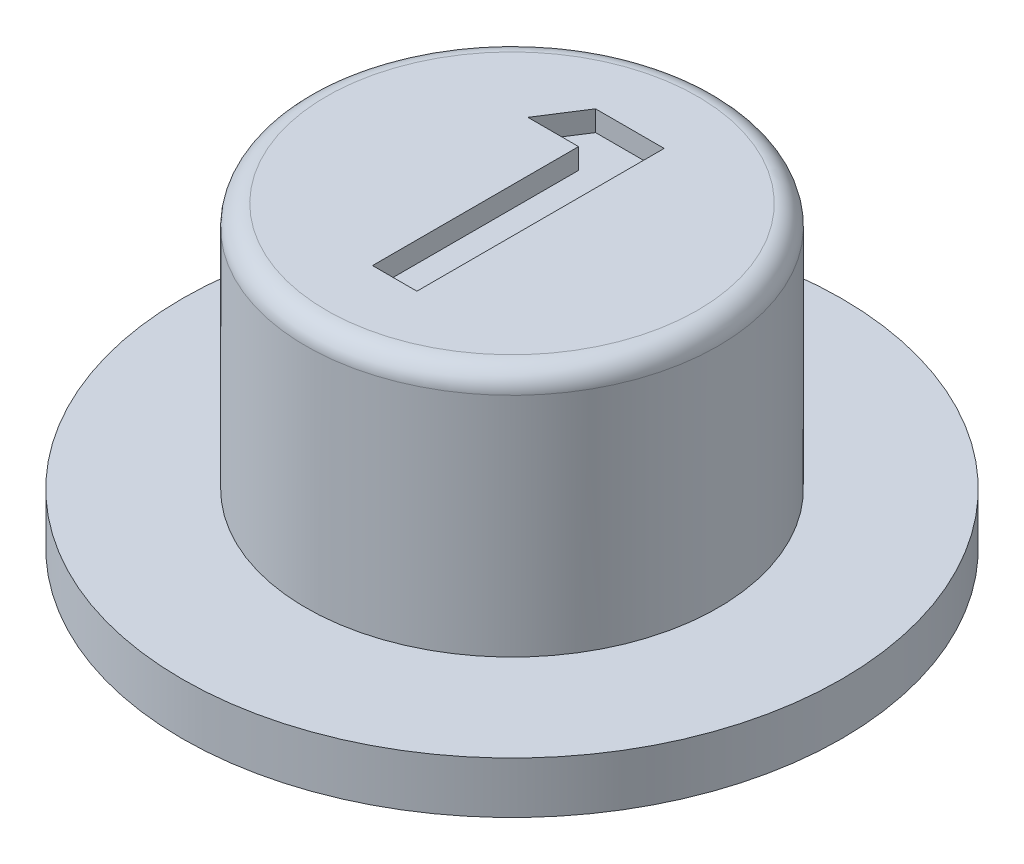
SolidWorks part; units mm, degrees
ref_plane "Front Plane" through (0, 0, 0) normal (0, 0, 1) x (1, 0, 0)
ref_plane "Top Plane" through (0, 0, 0) normal (0, 1, 0) x (1, 0, 0)
ref_plane "Right Plane" through (0, 0, 0) normal (1, 0, 0) x (0, 0, -1)
sketch "Sketch1" plane through (0, 0, 0) normal (0, 0, 1) x (1, 0, 0)
  line L1 (0, 7.25) -> (5, 7.25)
  line L2 (5, 7.25) -> (5, 1.25)
  line L3 (5, 1.25) -> (8, 1.25)
  line L4 (8, 1.25) -> (8, 0)
  line L6 (0, 7.25) -> (0, 6.9292) construction
  line L7 (0, 7.25) -> (0, 0)
  line L10 (0, 0) -> (8, 0)
  dimension "D1" = 5
  dimension "D2" = 3
  dimension "D3" = 6
  dimension "D4" = 1.25
revolve "Revolve1" add sketch "Sketch1" angle 360 about L6
sketch "Sketch2" plane through (0, 0, 0) normal (0, -1, 0) x (1, 0, 0)
  line L1 (-1.25, -1.75) -> (1.25, -1.75)
  line L2 (-1.25, -1.75) -> (-1.25, 1.75)
  line L3 (-1.25, 1.75) -> (1.25, 1.75)
  line L4 (1.25, -1.75) -> (1.25, 1.75)
  line L5 (-1.25, -1.75) -> (1.25, 1.75) construction
  line L6 (-1.25, 1.75) -> (1.25, -1.75) construction
  point P0 (0, 0)
  dimension "D1" = 2.5
  dimension "D2" = 3.5
extrude "Cut-Extrude1" cut sketch "Sketch2" against normal blind 3.5 contours L3 L4 L1 L2
fillet "Fillet1" radius 0.5 1 edges at (-5, 7.25, 0)
sketch "Sketch3" plane through (0, 7.25, 0) normal (0, 1, 0) x (1, 0, 0)
  line L0 (-3.3541, -3) -> (3.3541, -3) construction
  line L1 (0, 0) -> (0, -3) construction
  circle A0 centre (0, 0) radius 4.5 construction
  text T0 "1" font "Century Gothic" height 6
  dimension "D1" = 3
extrude "Cut-Extrude2" cut sketch "Sketch3" against normal blind 0.5
